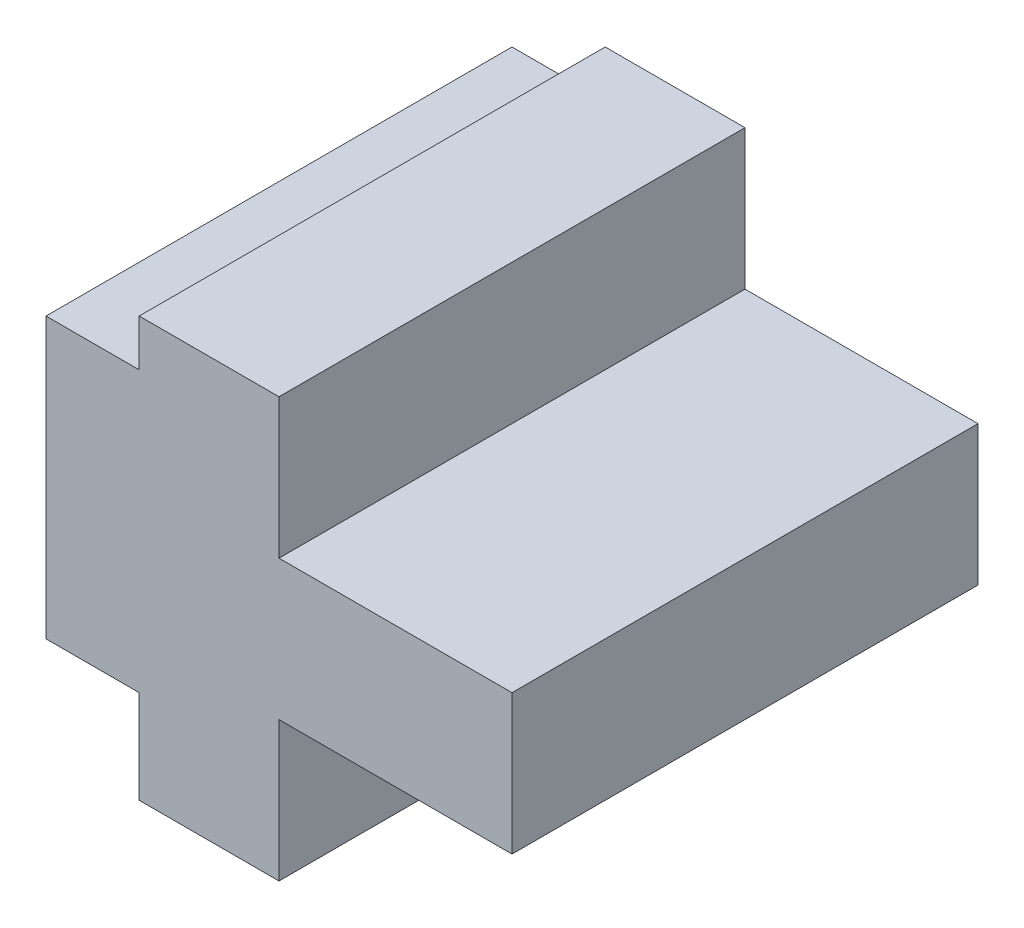
SolidWorks part; units mm, degrees
ref_plane "Front Plane" through (0, 0, 0) normal (0, 0, 1) x (1, 0, 0)
ref_plane "Top Plane" through (0, 0, 0) normal (0, 1, 0) x (1, 0, 0)
ref_plane "Right Plane" through (0, 0, 0) normal (1, 0, 0) x (0, 0, -1)
sketch "Sketch1" plane through (0, 0, 0) normal (0, 0, 1) x (1, 0, 0)
  line L0 (-5, 0) -> (5, 0) construction
  line L1 (-5, 2) -> (-5, 8)
  line L2 (-5, 2) -> (-3, 2)
  line L3 (-3, 2) -> (-3, 0)
  line L4 (-3, 0) -> (0, 0)
  line L5 (0, 0) -> (0, 3)
  line L6 (0, 3) -> (5, 3)
  line L7 (-5, 8) -> (-3, 8)
  line L8 (-3, 8) -> (-3, 9)
  line L9 (5, 3) -> (5, 6)
  line L10 (5, 6) -> (0, 6)
  line L11 (0, 6) -> (0, 9)
  line L12 (-3, 9) -> (0, 9)
  point P3 (0, 0)
  point P12 (-3, 8.5)
  dimension "D1" = 10
  dimension "D2" = 6
  dimension "D3" = 2
  dimension "D4" = 3
  dimension "D5" = 3
  dimension "D6" = 1
  dimension "D7" = 5
  dimension "D8" = 3
  dimension "D9" = 3
  dimension "D10" = 9
extrude "Boss-Extrude1" add sketch "Sketch1" along normal mid plane 10
